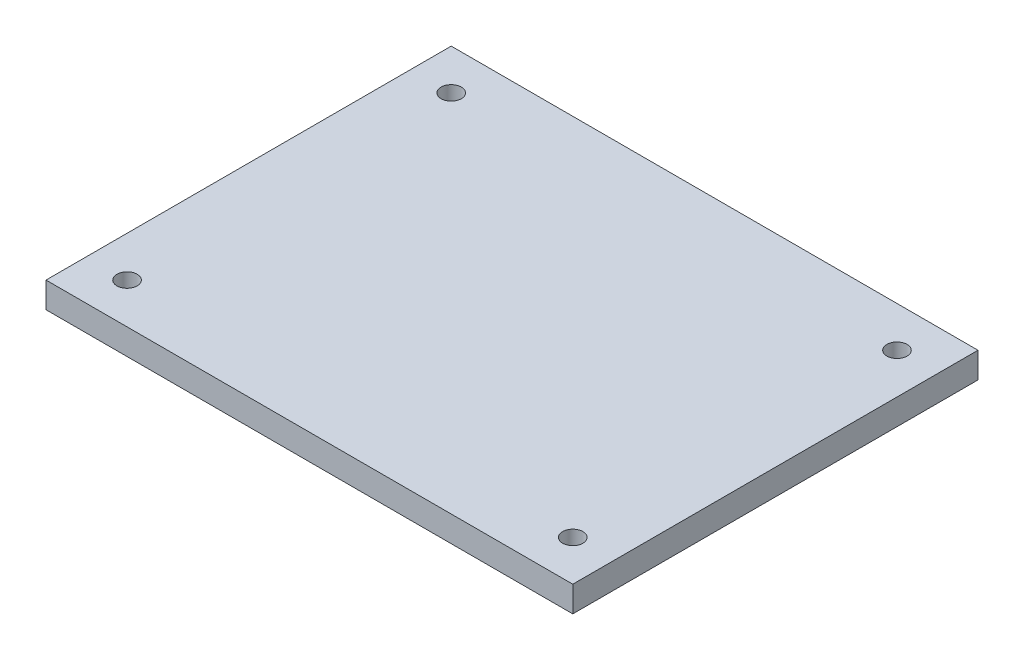
SolidWorks part; units mm, degrees
ref_plane "Front Plane" through (0, 0, 0) normal (0, 0, 1) x (1, 0, 0)
ref_plane "Top Plane" through (0, 0, 0) normal (0, 1, 0) x (1, 0, 0)
ref_plane "Right Plane" through (0, 0, 0) normal (1, 0, 0) x (0, 0, -1)
sketch "Sketch1" plane through (0, 0, 0) normal (0, 1, 0) x (1, 0, 0)
  line L1 (0, 0) -> (65, 0)
  line L2 (0, 0) -> (0, 50)
  line L3 (0, 50) -> (65, 50)
  line L4 (65, 0) -> (65, 50)
  dimension "D1" = 65
  dimension "D2" = 50
extrude "Boss-Extrude1" add sketch "Sketch1" along normal blind 3.175
hole_wizard "M3x0.5 Tapped Hole1" positions "Sketch3" profile "Sketch2" tap size "M3x0.5" standard "Ansi Metric"
sketch "Sketch3" plane through (0, 3.175, 0) normal (0, 1, 0) x (-1, 0, 0)
  line L0 (0, -50) -> (0, 0) construction
  line L1 (0, 0) -> (-65, 0) construction
  line L2 (-65, -50) -> (0, -50) construction
  line L3 (-65, 0) -> (-65, -50) construction
  point P0 (-5, -45)
  point P1 (-60, -45)
  point P3 (-60, -5)
  point P5 (-5, -5)
  dimension "D1" = 5
  dimension "D2" = 5
  dimension "D3" = 5
  dimension "D4" = 5
  dimension "D5" = 5
  dimension "D6" = 5
  dimension "D7" = 5
  dimension "D8" = 5
sketch "Sketch2" plane through (5, 3.175, -45) normal (1, 0, 0) x (0, 0, 1)
  line L0 (0, 0) -> (0, 8.2511)
  line L1 (0, 8.2511) -> (1.25, 7.5)
  line L2 (1.25, 7.5) -> (1.25, 0)
  line L5 (1.25, 0) -> (0, 0)
  line L10 (0, 8.2511) -> (-1.25, 7.5) construction
  line L11 (0, -6.35) -> (0, 107.95) construction
  dimension "Tap Drill Dia." = 2.5
  dimension "Tap Drill Depth" = 7.5
  dimension "Drill Angle" = 118
cosmetic thread "Hole Thread1" parameters "D1"=3.175, "D2"=3
cosmetic thread "Hole Thread2" parameters "D1"=3.175, "D2"=3
cosmetic thread "Hole Thread3" parameters "D1"=3.175, "D2"=3
cosmetic thread "Hole Thread4" parameters "D1"=3.175, "D2"=3
